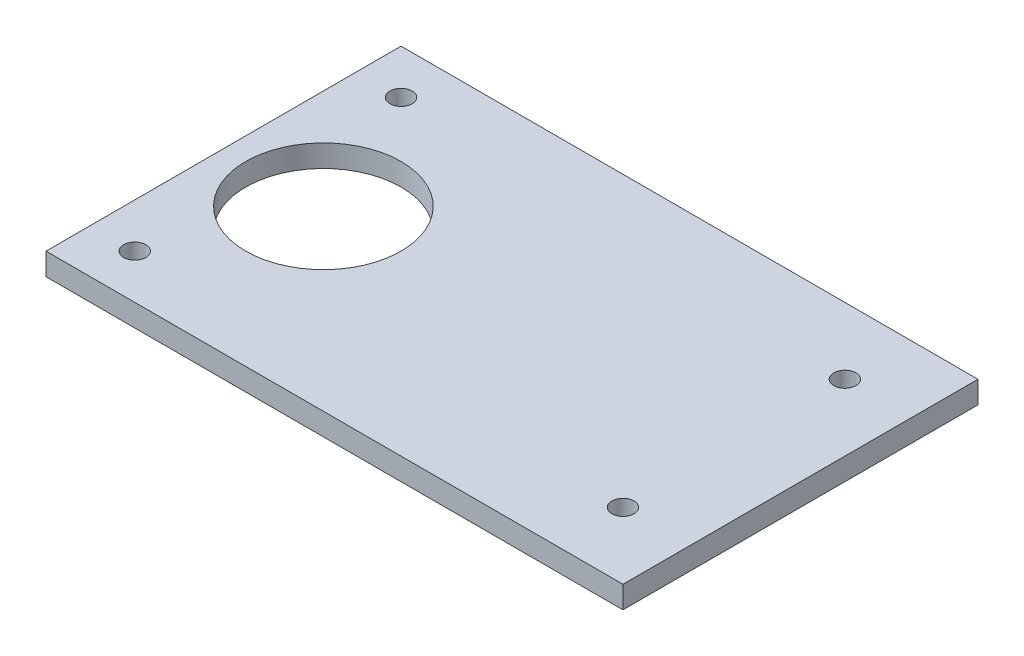
SolidWorks part; units mm, degrees
ref_plane "Front Plane" through (0, 0, 0) normal (0, 0, 1) x (1, 0, 0)
ref_plane "Top Plane" through (0, 0, 0) normal (0, 1, 0) x (1, 0, 0)
ref_plane "Right Plane" through (0, 0, 0) normal (1, 0, 0) x (0, 0, -1)
sketch "Sketch1" plane through (0, 0, 0) normal (0, 1, 0) x (1, 0, 0)
  line L0 (-69.7183, -5.3521) -> (60.2817, -5.3521) construction
  line L1 (-69.7183, 34.6479) -> (60.2817, 34.6479)
  line L2 (-69.7183, 34.6479) -> (-69.7183, -45.3521)
  line L3 (-69.7183, -45.3521) -> (60.2817, -45.3521)
  line L4 (60.2817, 34.6479) -> (60.2817, -45.3521)
  circle A0 centre (-47.2183, -5.3521) radius 17.5
  circle A1 centre (45.2817, 19.6479) radius 2.5
  circle A2 centre (-59.7183, 24.6479) radius 2.5
  circle A3 centre (45.2817, -30.3521) radius 2.5
  circle A4 centre (-59.7183, -35.3521) radius 2.5
  point P12 (0, 0)
  dimension "D3" = 35
  dimension "D4" = 5
  dimension "D5" = 5
  dimension "D6" = 15
  dimension "D7" = 15
  dimension "D8" = 10
  dimension "D9" = 10
  dimension "D10" = 22.5
  dimension "D1" = 130
  dimension "D2" = 80
extrude "Boss-Extrude1" add sketch "Sketch1" along normal blind 5
